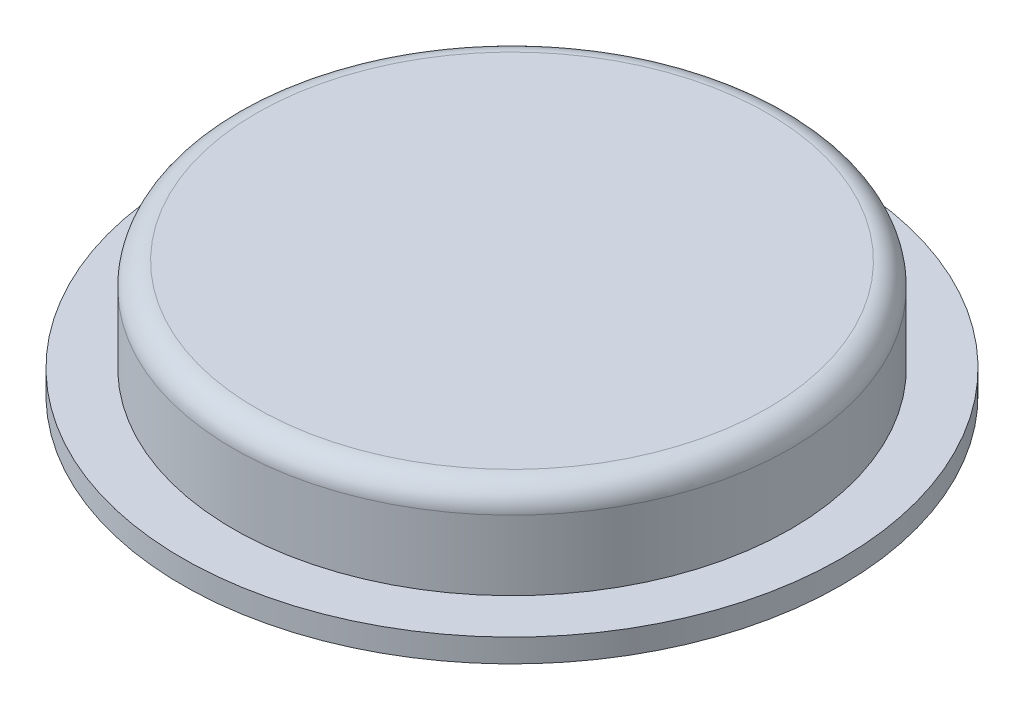
SolidWorks part; units mm, degrees
ref_plane "Спереди" through (0, 0, 0) normal (0, 0, 1) x (1, 0, 0)
ref_plane "Сверху" through (0, 0, 0) normal (0, 1, 0) x (1, 0, 0)
ref_plane "Справа" through (0, 0, 0) normal (1, 0, 0) x (0, 0, -1)
other "Configuration Table"
sketch "Эскиз1" plane through (0, 0, 0) normal (0, 0, 1) x (1, 0, 0)
  line L0 (-5.296, 0) -> (-7.0918, 0)
  line L1 (-7.0918, 0) -> (-7.0918, 0.5)
  line L2 (-7.0918, 0.5) -> (-6, 0.5)
  line L3 (-6, 0.5) -> (-6, 2.5)
  line L5 (-6, 2.5) -> (0, 2.5)
  line L6 (0, 2.5) -> (0, 1.3406)
  line L8 (0, 1.3406) -> (-5.296, 1.3406)
  line L11 (-5.296, 1.3406) -> (-5.296, 0)
  dimension "D1" = 6
  dimension "D2" = 2
  dimension "D3" = 0.5
revolve "Повернуть1" add sketch "Эскиз1" angle 360 about L6
fillet "Скругление1" radius 0.5 1 edges at (-6, 2.5, 0)
